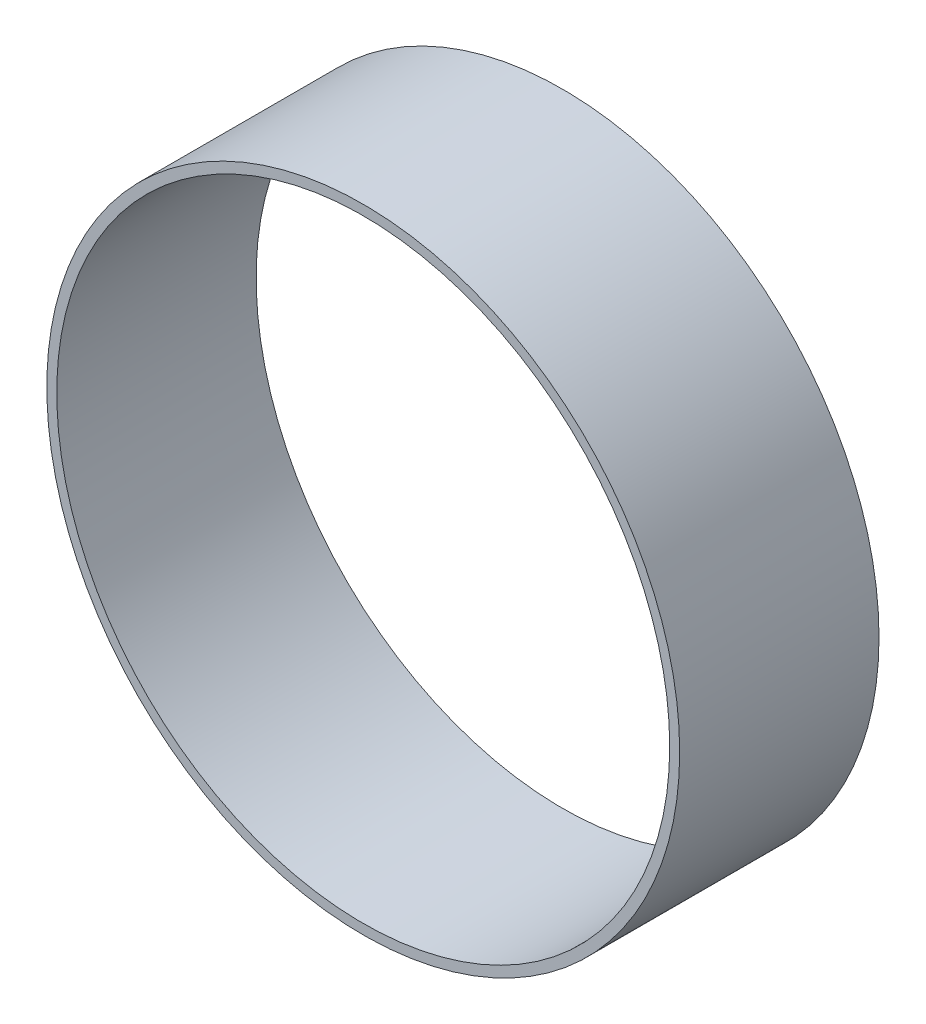
SolidWorks part; units mm, degrees
material "PVC"
ref_plane "Front" through (0, 0, 0) normal (0, 0, 1) x (1, 0, 0)
ref_plane "Top" through (0, 0, 0) normal (0, 1, 0) x (1, 0, 0)
ref_plane "Right" through (0, 0, 0) normal (1, 0, 0) x (0, 0, -1)
sketch "Sketch1" plane through (0, 0, 0) normal (0, 0, 1) x (1, 0, 0)
  circle A0 centre (0, 0) radius 63.5
  circle A1 centre (0, 0) radius 61.5
  dimension "D1" = 127
  dimension "D2" = 2
extrude "Boss-Extrude1" add sketch "Sketch1" along normal blind 40
